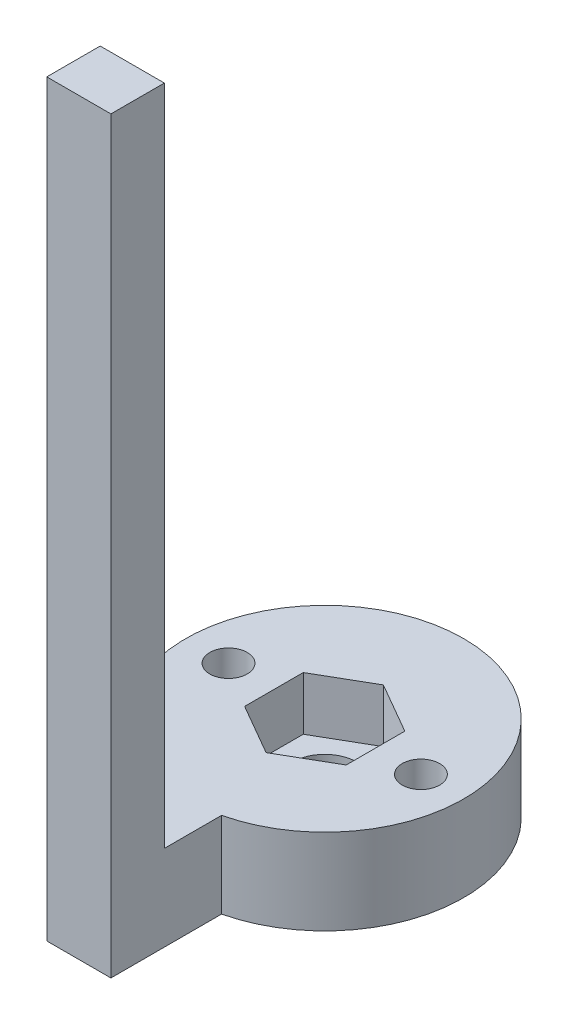
SolidWorks part; units mm, degrees
ref_plane "Front Plane" through (0, 0, 0) normal (0, 0, 1) x (1, 0, 0)
ref_plane "Top Plane" through (0, 0, 0) normal (0, 1, 0) x (1, 0, 0)
ref_plane "Right Plane" through (0, 0, 0) normal (1, 0, 0) x (0, 0, -1)
sketch "Sketch1" plane through (0, 0, 0) normal (0, 1, 0) x (1, 0, 0)
  circle A0 centre (0, 0) radius 13
  dimension "D1" = 26
extrude "Boss-Extrude1" add sketch "Sketch1" along normal blind 8
sketch "Sketch2" plane through (0, 8, 0) normal (0, 1, 0) x (1, 0, 0)
  line L1 (0, 5.4848) -> (-4.75, 2.7424)
  line L2 (-4.75, 2.7424) -> (-4.75, -2.7424)
  line L3 (-4.75, -2.7424) -> (0, -5.4848)
  line L4 (0, -5.4848) -> (4.75, -2.7424)
  line L5 (4.75, -2.7424) -> (4.75, 2.7424)
  line L6 (4.75, 2.7424) -> (0, 5.4848)
  circle A0 centre (0, 0) radius 4.75 construction
extrude "Cut-Extrude1" cut sketch "Sketch2" against normal blind 5 contours L6 L1 L2 L3 L4 L5
sketch "Sketch3" plane through (0, 8, 0) normal (0, 1, 0) x (1, 0, 0)
  line L1 (0, 0) -> (18, 0)
  line L2 (18, 0) -> (-15.6102, 0)
  circle A0 centre (9, 0) radius 1.75
  circle A1 centre (0, 0) radius 13 construction
  point P9 (0, 0)
  dimension "D1" = 3.5
  dimension "D3" = 9
extrude "Cut-Extrude2" cut sketch "Sketch3" against normal through all contours A0
mirror "Mirror1" about plane through (0, 0, 0) normal (1, 0, 0) of "Cut-Extrude2"
sketch "Sketch4" plane through (0, 3, 0) normal (0, 1, 0) x (1, 0, 0)
  circle A0 centre (0, 0) radius 3
  dimension "D1" = 6
extrude "Cut-Extrude3" cut sketch "Sketch4" against normal blind 5
ref_plane "Plane5" through (0, 0, 13) normal (0, 0, 1) x (0, -1, 0)
sketch "Sketch5" plane through (0, 0, 13) normal (0, 0, 1) x (0, -1, 0)
  line L0 (0.3047, 0) -> (-19.8124, 0)
  line L1 (0, -3) -> (-8, -3)
  line L2 (0, -3) -> (0, 3)
  line L3 (0, 3) -> (-8, 3)
  line L4 (-8, -3) -> (-8, 3)
  line L5 (-8, 13) -> (-8, -13) construction
  line L6 (0, -13) -> (0, 13) construction
  dimension "D1" = 6
  dimension "D2" = 3
sketch "Sketch6" plane through (0, 0, 0) normal (0, -1, 0) x (1, 0, 0)
  circle A0 centre (9, 0) radius 3
  dimension "D1" = 6
extrude "Cut-Extrude4" cut sketch "Sketch6" against normal blind 3
sketch "Sketch7" plane through (0, 0, 0) normal (0, -1, 0) x (1, 0, 0)
  circle A0 centre (-9, 0) radius 3
  dimension "D1" = 6
extrude "Cut-Extrude5" cut sketch "Sketch7" against normal blind 3 contours A0
extrude "Boss-Extrude2" add sketch "Sketch5" along normal mid plane 10 contours L1 L4 L3 L2
sketch "Sketch8" plane through (0, 0, 18) normal (0, 0, 1) x (1, 0, 0)
  line L0 (-3, 0) -> (-3, 8) construction
  line L1 (3, 0) -> (-3, 0)
  line L2 (3, 0) -> (3, 70)
  line L3 (3, 70) -> (-3, 70)
  line L4 (-3, 0) -> (-3, 70)
  dimension "D1" = 70
extrude "Boss-Extrude3" add sketch "Sketch8" along normal blind 5
